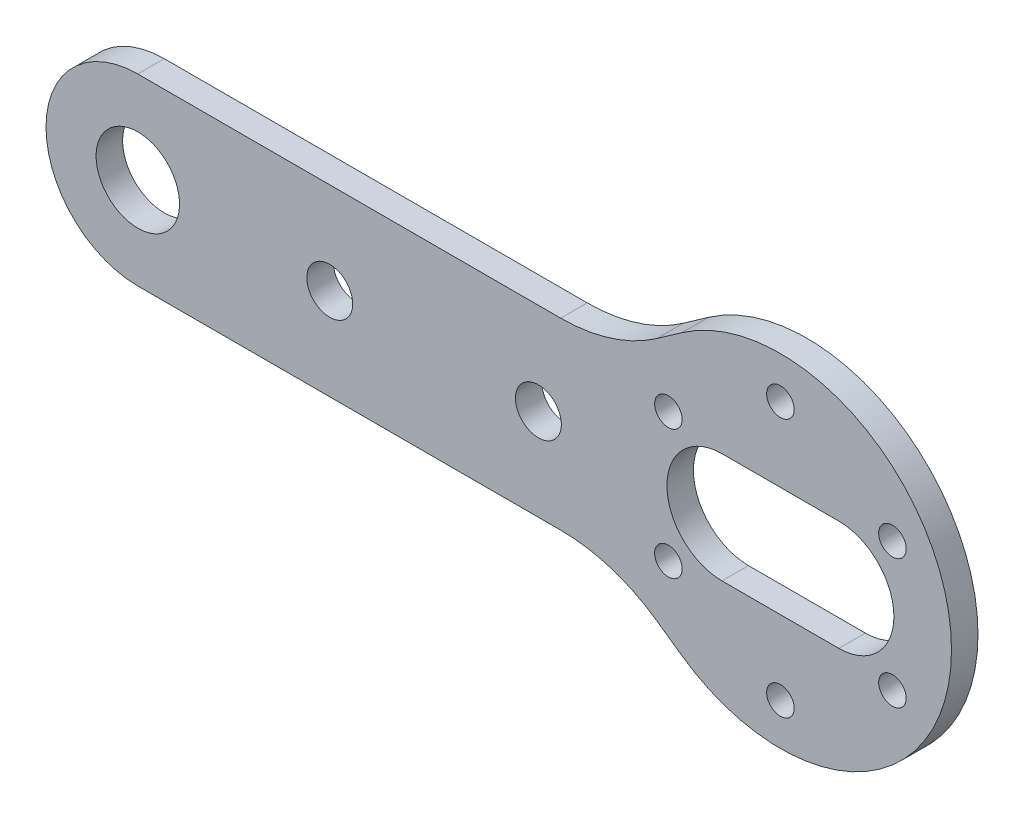
SolidWorks part; units mm, degrees
ref_plane "Alzado" through (0, 0, 0) normal (0, 0, 1) x (1, 0, 0)
ref_plane "Planta" through (0, 0, 0) normal (0, 1, 0) x (1, 0, 0)
ref_plane "Vista lateral" through (0, 0, 0) normal (1, 0, 0) x (0, 0, -1)
sketch "Croquis2" plane through (0, 0, 64.2039) normal (0, 0, 1) x (1, 0, 0)
  line L0 (87.351, 14.5776) -> (101.351, 14.5776) construction
  line L1 (87.351, 21.1776) -> (101.351, 21.1776)
  line L2 (87.351, 7.9776) -> (101.351, 7.9776)
  line L5 (82.563, 31.3494) -> (74.351, 25.5776)
  line L6 (74.351, 25.5776) -> (17.351, 25.5776)
  line L8 (17.351, 3.5776) -> (74.351, 3.5776)
  line L9 (74.351, 3.5776) -> (82.563, -2.1941)
  line L10 (6.351, 14.5776) -> (114.851, 14.5776) construction
  circle A0 centre (94.351, 14.5776) radius 15.5 construction
  circle A1 centre (94.351, -0.9224) radius 1.65
  circle A2 centre (80.9276, 6.8276) radius 1.65
  circle A3 centre (80.9276, 22.3276) radius 1.65
  circle A4 centre (94.351, 30.0776) radius 1.65
  circle A5 centre (107.7744, 22.3276) radius 1.65
  circle A6 centre (107.7744, 6.8276) radius 1.65
  arc A7 (87.351, 21.1776) -> (87.351, 7.9776) centre (87.351, 14.5776) ccw
  arc A8 (101.351, 7.9776) -> (101.351, 21.1776) centre (101.351, 14.5776) ccw
  arc A9 (82.563, 31.3494) -> (82.563, -2.1941) centre (94.351, 14.5776) cw
  circle A12 centre (17.351, 14.5776) radius 5
  arc A13 (17.351, 25.5776) -> (17.351, 3.5776) centre (17.351, 14.5776) ccw
  point P19 (94.351, 14.5776)
  point P20 (94.351, 14.5776)
  point P28 (94.351, 14.5776)
  dimension "D2" = 31
  dimension "D3" = 3.3
  dimension "D1" = 5
  dimension "D8" = 10
  dimension "D9" = 11
  dimension "D5" = 14
  dimension "D6" = 13.2
  dimension "D7" = 20
  dimension "D10" = 70
  dimension "D4" = 6
extrude "Saliente-Extruir1" add sketch "Croquis2" along normal blind 3.175
hole_wizard "Taladro de margen para M51" positions "Croquis6" profile "Croquis5" hole size "M5" standard "Ansi Metric"
sketch "Croquis6" plane through (0, 0, 64.2039) normal (0, 0, -1) x (-1, 0, 0)
  circle A0 centre (-17.351, 14.5776) radius 5 construction
  point P0 (-65.351, 14.5776)
  point P2 (-40.351, 14.5776)
  dimension "D1" = 23
  dimension "D2" = 25
sketch "Croquis5" plane through (65.351, 14.5776, 64.2039) normal (1, 0, 0) x (0, 1, 0)
  line L0 (0, 0) -> (0, 7.6524)
  line L1 (0, 7.6524) -> (2.75, 6)
  line L2 (2.75, 6) -> (2.75, 0)
  line L5 (2.75, 0) -> (0, 0)
  line L10 (0, 7.6524) -> (-2.75, 6) construction
  line L11 (0, -6.35) -> (0, 107.95) construction
  dimension "Diámetro de taladro" = 5.5
  dimension "Profundidad de taladro" = 6
  dimension "Ángulo de perforador" = 118
fillet "Redondeo1" radius 20 2 edges at (74.351, 3.5776, 65.7914) (74.351, 25.5776, 65.7914)
